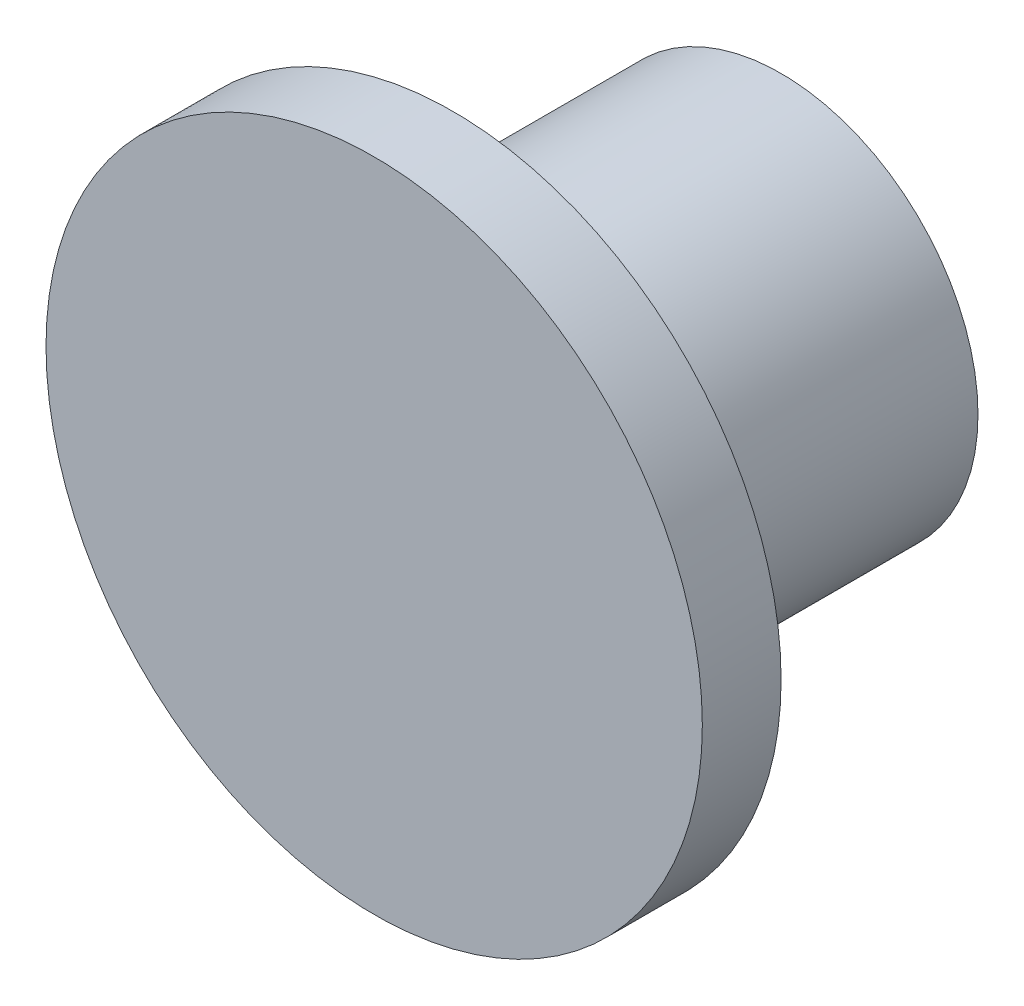
SolidWorks part; units mm, degrees
ref_plane "Front Plane" through (0, 0, 0) normal (0, 0, 1) x (1, 0, 0)
ref_plane "Top Plane" through (0, 0, 0) normal (0, 1, 0) x (1, 0, 0)
ref_plane "Right Plane" through (0, 0, 0) normal (1, 0, 0) x (0, 0, -1)
sketch "Sketch1" plane through (0, 0, 0) normal (0, 0, 1) x (1, 0, 0)
  circle A0 centre (0, 0) radius 19.05
  dimension "D1" = 38.1
extrude "Boss-Extrude1" add sketch "Sketch1" along normal blind 31.75 contours A0
sketch "Sketch2" plane through (0, 0, 31.75) normal (0, 0, 1) x (1, 0, 0)
  circle A0 centre (0, 0) radius 31.75
  dimension "D1" = 63.5
extrude "Boss-Extrude2" add sketch "Sketch2" along normal blind 7.62
